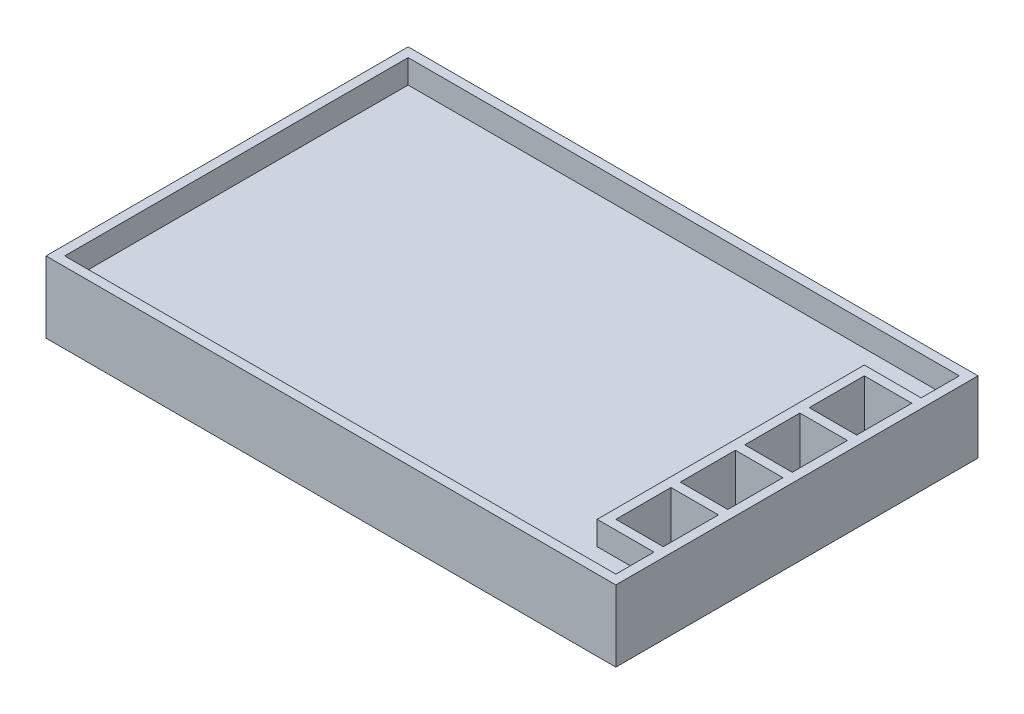
SolidWorks part; units mm, degrees
ref_plane "Front Plane" through (0, 0, 0) normal (0, 0, 1) x (1, 0, 0)
ref_plane "Top Plane" through (0, 0, 0) normal (0, 1, 0) x (1, 0, 0)
ref_plane "Right Plane" through (0, 0, 0) normal (1, 0, 0) x (0, 0, -1)
sketch "Sketch1" plane through (0, 0, 0) normal (0, 1, 0) x (1, 0, 0)
  line L1 (-272.4428, 268.4165) -> (337.1572, 268.4165)
  line L2 (-272.4428, 268.4165) -> (-272.4428, -118.9835)
  line L3 (-272.4428, -118.9835) -> (337.1572, -118.9835)
  line L4 (337.1572, 268.4165) -> (337.1572, -118.9835)
  dimension "D1" = 609.6
  dimension "D2" = 387.4
extrude "Boss-Extrude1" add sketch "Sketch1" against normal blind 76.2
sketch "Sketch2" plane through (0, 0, 0) normal (0, 1, 0) x (1, 0, 0)
  line L0 (-272.4428, 268.4165) -> (-272.4428, -118.9835) construction
  line L1 (-262.4428, 258.4165) -> (327.1572, 258.4165)
  line L2 (-262.4428, 258.4165) -> (-262.4428, -108.9835)
  line L3 (-262.4428, -108.9835) -> (327.1572, -108.9835)
  line L4 (327.1572, 258.4165) -> (327.1572, -108.9835)
  line L5 (-272.4428, -118.9835) -> (337.1572, -118.9835) construction
  line L6 (337.1572, -118.9835) -> (337.1572, 268.4165) construction
  line L7 (337.1572, 268.4165) -> (-272.4428, 268.4165) construction
  dimension "D1" = 10
  dimension "D2" = 10
  dimension "D3" = 10
  dimension "D4" = 10
extrude "Cut-Extrude1" cut sketch "Sketch2" against normal offset from surface (25.4 mm away) 25.4 up to face at (32.3572, 0, -74.7165)
sketch "Sketch3" plane through (0, -25.4, 0) normal (0, 1, 0) x (1, 0, 0)
  line L0 (384.8029, 74.7165) -> (-352.974, 74.7165) construction
  line L1 (-262.4428, 258.4165) -> (327.1572, 258.4165) construction
  line L2 (-262.4428, -108.9835) -> (327.1572, -108.9835) construction
  line L3 (327.1572, 258.4165) -> (327.1572, -108.9835) construction
  line L4 (327.1572, 207.6165) -> (276.3572, 207.6165)
  line L5 (327.1572, 207.6165) -> (327.1572, 148.6665)
  line L6 (327.1572, 148.6665) -> (276.3572, 148.6665)
  line L7 (276.3572, 207.6165) -> (276.3572, 148.6665)
  line L8 (327.1572, -108.9835) -> (327.1572, 258.4165) construction
  line L9 (327.1572, 138.6665) -> (276.3572, 138.6665)
  line L10 (327.1572, 138.6665) -> (327.1572, 79.7165)
  line L11 (327.1572, 79.7165) -> (276.3572, 79.7165)
  line L12 (276.3572, 138.6665) -> (276.3572, 79.7165)
  line L13 (327.1572, 69.7165) -> (276.3572, 69.7165)
  line L14 (327.1572, 69.7165) -> (327.1572, 10.7665)
  line L15 (327.1572, 10.7665) -> (276.3572, 10.7665)
  line L16 (276.3572, 69.7165) -> (276.3572, 10.7665)
  line L17 (327.1572, -108.9835) -> (-262.4428, -108.9835) construction
  line L18 (327.1572, 0.7665) -> (276.3572, 0.7665)
  line L19 (327.1572, 0.7665) -> (327.1572, -58.1835)
  line L20 (327.1572, -58.1835) -> (276.3572, -58.1835)
  line L21 (276.3572, 0.7665) -> (276.3572, -58.1835)
  dimension "D1" = 10
  dimension "D2" = 10
  dimension "D3" = 10
  dimension "D4" = 50.8
  dimension "D5" = 50.8
extrude "Cut-Extrude2" cut sketch "Sketch3" against normal offset from surface (35.8 mm away) 15 up to face at (32.3572, -76.2, -74.7165)
sketch "Sketch7" plane through (0, -25.4, 0) normal (0, 1, 0) x (1, 0, 0)
  line L0 (327.1572, 217.6165) -> (266.3572, 217.6165)
  line L1 (327.1572, 258.4165) -> (327.1572, 207.6165) construction
  line L2 (266.3572, 217.6165) -> (266.3572, -68.1835)
  line L3 (266.3572, -68.1835) -> (327.1572, -68.1835)
  line L4 (327.1572, -58.1835) -> (327.1572, -108.9835) construction
  line L5 (327.1572, -68.1835) -> (327.1572, -58.1835)
  line L6 (327.1572, -58.1835) -> (276.3572, -58.1835)
  line L7 (276.3572, -58.1835) -> (276.3572, 0.7665)
  line L8 (276.3572, 0.7665) -> (327.1572, 0.7665)
  line L9 (327.1572, 0.7665) -> (327.1572, 10.7665)
  line L10 (327.1572, 10.7665) -> (276.3572, 10.7665)
  line L11 (276.3572, 10.7665) -> (276.3572, 69.7165)
  line L12 (276.3572, 69.7165) -> (327.1572, 69.7165)
  line L13 (327.1572, 69.7165) -> (327.1572, 79.7165)
  line L14 (327.1572, 79.7165) -> (276.3572, 79.7165)
  line L15 (276.3572, 79.7165) -> (276.3572, 138.6665)
  line L16 (276.3572, 138.6665) -> (327.1572, 138.6665)
  line L17 (327.1572, 138.6665) -> (327.1572, 148.6665)
  line L18 (327.1572, 148.6665) -> (276.3572, 148.6665)
  line L19 (276.3572, 148.6665) -> (276.3572, 207.6165)
  line L20 (276.3572, 207.6165) -> (327.1572, 207.6165)
  line L21 (327.1572, 207.6165) -> (327.1572, 217.6165)
  dimension "D1" = 10
  dimension "D2" = 10
  dimension "D3" = 10
extrude "Boss-Extrude2" add sketch "Sketch7" along normal up to surface (25.4 mm away) up to face at (32.3572, 0, -74.7165)
